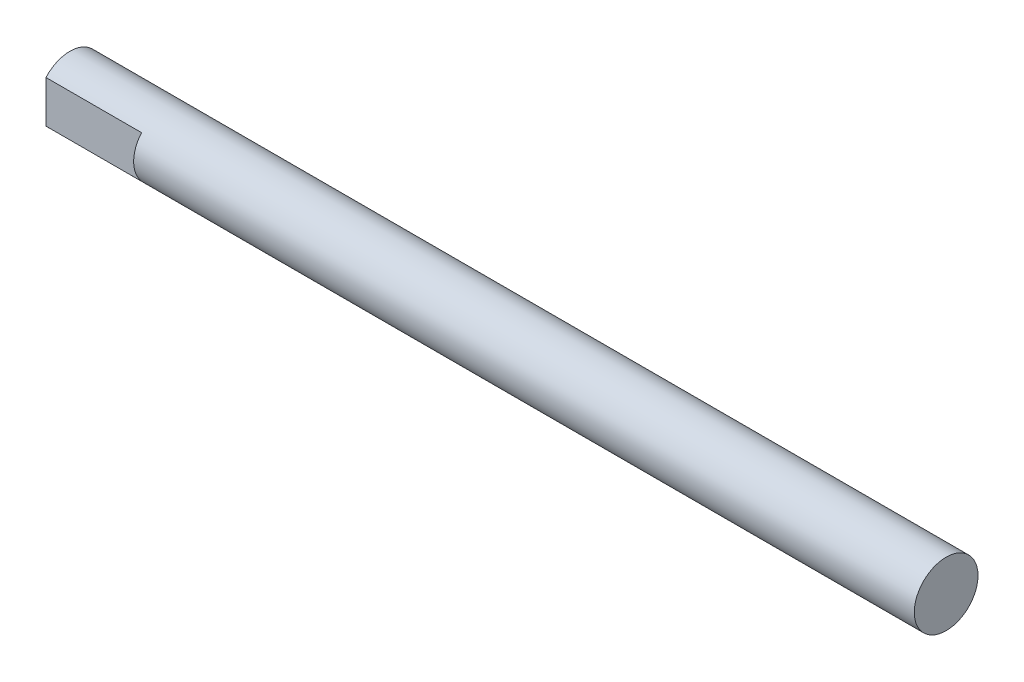
SolidWorks part; units mm, degrees
ref_plane "Front Plane" through (0, 0, 0) normal (1, 0, 0) x (0, 1, 0)
ref_plane "Top Plane" through (0, 0, 0) normal (0, 0, 1) x (0, 1, 0)
ref_plane "Right Plane" through (0, 0, 0) normal (0, 1, 0) x (-1, 0, 0)
sketch "Sketch1" plane through (0, 0, 0) normal (1, 0, 0) x (0, 1, 0)
  circle A0 centre (0, 0) radius 2
  dimension "D1" = 4
extrude "Boss-Extrude1" add sketch "Sketch1" along normal blind 55
sketch "Sketch2" plane through (0, 0, 0) normal (-1, 0, 0) x (0, -1, 0)
  line L0 (-1.3229, 1.5) -> (1.3229, 1.5)
  circle A0 centre (0, 0) radius 2 construction
  arc A1 (1.3229, 1.5) -> (-1.3229, 1.5) centre (0, 0) ccw
  dimension "D1" = 1.5
extrude "Cut-Extrude1" cut sketch "Sketch2" against normal blind 6
